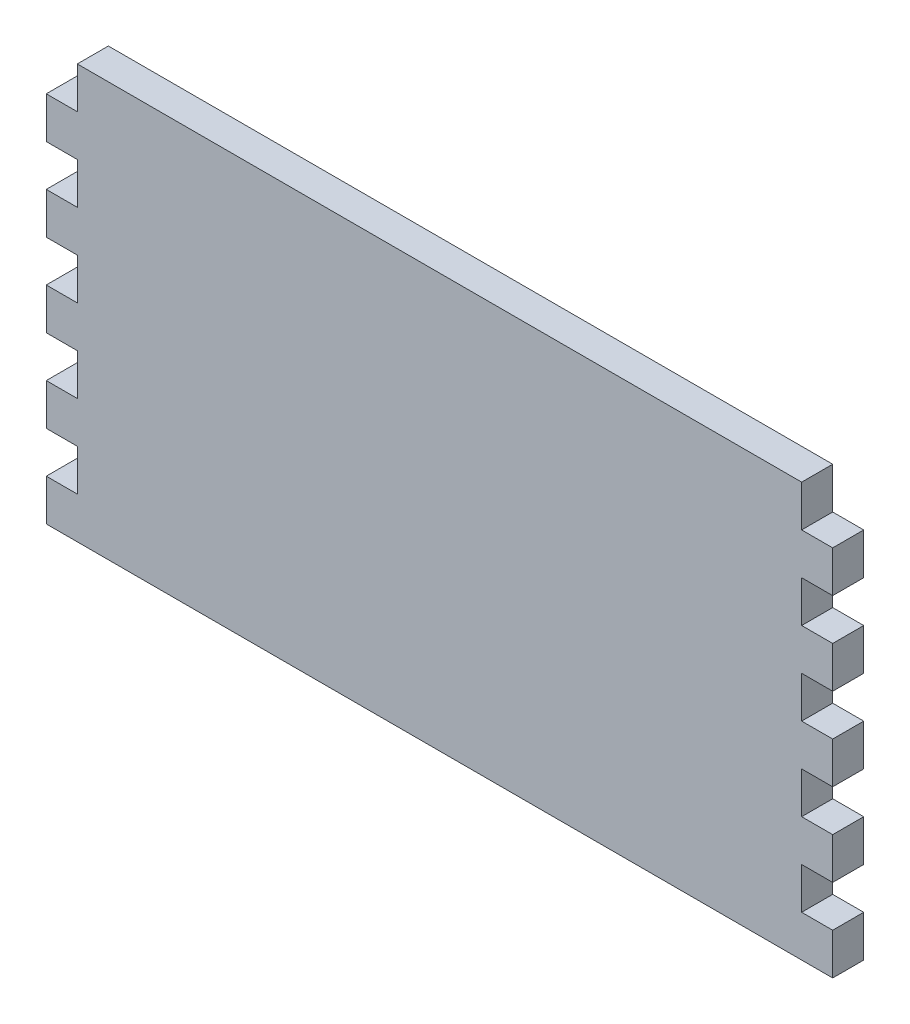
SolidWorks part; units mm, degrees
ref_plane "Plan de face" through (0, 0, 0) normal (0, 0, 1) x (1, 0, 0)
ref_plane "Plan de dessus" through (0, 0, 0) normal (0, 1, 0) x (1, 0, 0)
ref_plane "Plan de droite" through (0, 0, 0) normal (1, 0, 0) x (0, 0, -1)
sketch "Esquisse1" plane through (0, 0, 0) normal (0, 0, 1) x (1, 0, 0)
  line L0 (-14.6083, 25.4102) -> (-14.6083, -14.5898) construction
  line L1 (-49.6083, 25.4102) -> (20.3917, 25.4102)
  line L2 (-49.6083, 25.4102) -> (-49.6083, 21.4102)
  line L3 (-49.6083, -14.5898) -> (20.3917, -14.5898)
  line L4 (20.3917, 25.4102) -> (20.3917, 21.4102)
  line L5 (-49.6083, 13.4102) -> (-52.6083, 13.4102)
  line L6 (-49.6083, 21.4102) -> (-52.6083, 21.4102)
  line L7 (-49.6083, 9.4102) -> (-49.6083, 5.4102)
  line L8 (-49.6083, 17.4102) -> (-52.6083, 17.4102)
  line L9 (-52.6083, 21.4102) -> (-52.6083, 17.4102)
  line L10 (-52.6083, 13.4102) -> (-52.6083, 9.4102)
  line L11 (-49.6083, 9.4102) -> (-52.6083, 9.4102)
  line L12 (-49.6083, 5.4102) -> (-52.6083, 5.4102)
  line L13 (-52.6083, 5.4102) -> (-52.6083, 1.4102)
  line L14 (-49.6083, 1.4102) -> (-52.6083, 1.4102)
  line L15 (-49.6083, -2.5898) -> (-52.6083, -2.5898)
  line L16 (-52.6083, -2.5898) -> (-52.6083, -6.5898)
  line L17 (-49.6083, -6.5898) -> (-52.6083, -6.5898)
  line L18 (-49.6083, -10.5898) -> (-52.6083, -10.5898)
  line L19 (-52.6083, -10.5898) -> (-52.6083, -14.5898)
  line L20 (-49.6083, -14.5898) -> (-52.6083, -14.5898)
  line L21 (20.3917, -14.5898) -> (23.3917, -14.5898)
  line L22 (23.3917, -10.5898) -> (23.3917, -14.5898)
  line L23 (20.3917, -10.5898) -> (23.3917, -10.5898)
  line L24 (20.3917, -6.5898) -> (23.3917, -6.5898)
  line L25 (23.3917, -2.5898) -> (23.3917, -6.5898)
  line L26 (20.3917, -2.5898) -> (23.3917, -2.5898)
  line L27 (20.3917, 1.4102) -> (23.3917, 1.4102)
  line L28 (23.3917, 5.4102) -> (23.3917, 1.4102)
  line L29 (20.3917, 5.4102) -> (23.3917, 5.4102)
  line L30 (20.3917, 9.4102) -> (23.3917, 9.4102)
  line L31 (23.3917, 13.4102) -> (23.3917, 9.4102)
  line L32 (20.3917, 13.4102) -> (23.3917, 13.4102)
  line L33 (23.3917, 21.4102) -> (23.3917, 17.4102)
  line L34 (20.3917, 17.4102) -> (23.3917, 17.4102)
  line L35 (20.3917, 21.4102) -> (23.3917, 21.4102)
  line L36 (-49.6083, 17.4102) -> (-49.6083, 13.4102)
  line L37 (-49.6083, 1.4102) -> (-49.6083, -2.5898)
  line L38 (-49.6083, -6.5898) -> (-49.6083, -10.5898)
  line L39 (20.3917, 17.4102) -> (20.3917, 13.4102)
  line L40 (20.3917, 9.4102) -> (20.3917, 5.4102)
  line L41 (20.3917, 1.4102) -> (20.3917, -2.5898)
  line L42 (20.3917, -6.5898) -> (20.3917, -10.5898)
  dimension "D1" = 70
  dimension "D2" = 40
  dimension "D3" = 3
  dimension "D4" = 4
  dimension "D5" = 4
  dimension "D6" = 5
extrude "Boss.-Extru.1" add sketch "Esquisse1" along normal blind 3
